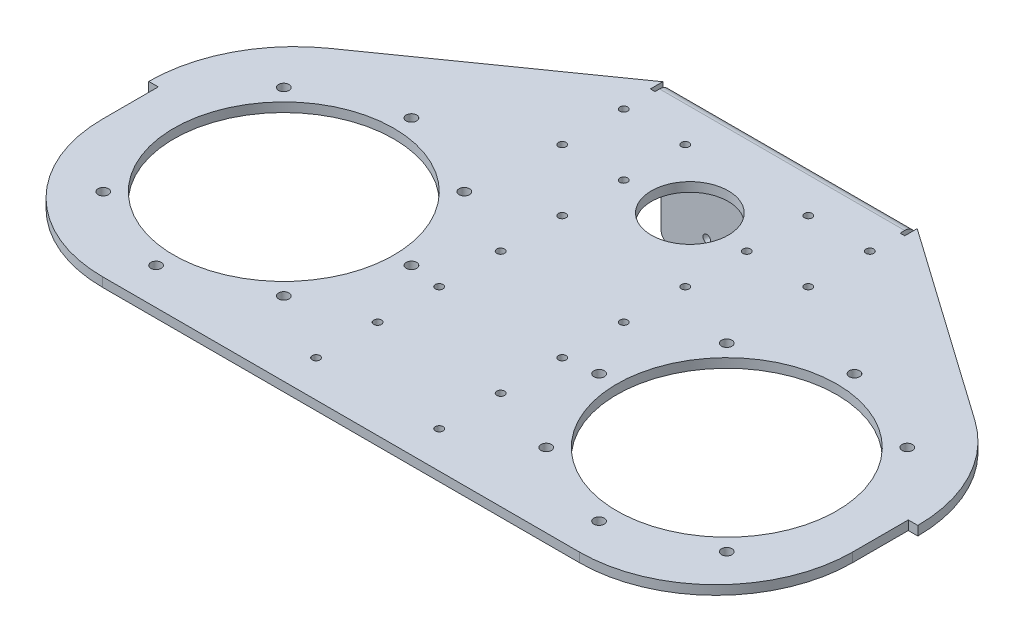
SolidWorks part; units mm, degrees
ref_plane "Спереди" through (0, 0, 0) normal (0, 0, 1) x (1, 0, 0)
ref_plane "Сверху" through (0, 0, 0) normal (0, 1, 0) x (1, 0, 0)
ref_plane "Справа" through (0, 0, 0) normal (1, 0, 0) x (0, 0, -1)
ref_plane "Плоскость4" through (0, 3, 0) normal (0, 1, 0) x (1, 0, 0)
sketch "Эскиз1" plane through (0, 3, 0) normal (0, 1, 0) x (1, 0, 0)
  line L0 (-124.9999, 9.1) -> (124.9999, 9.1)
  line L1 (104.8475, 47.8377) -> (41.3416, 92.5553)
  line L2 (41.3416, 92.5553) -> (41.3416, 88.5)
  line L3 (41.3416, 88.5) -> (-41.3416, 88.5)
  line L4 (-41.3416, 88.5) -> (-41.3416, 92.5553)
  line L5 (-41.3416, 92.5553) -> (-104.8475, 47.8377)
  arc A0 (124.9999, 9.1) -> (104.8475, 47.8377) centre (77.5, 9) ccw
  arc A1 (-104.8475, 47.8377) -> (-124.9999, 9.1) centre (-77.5, 9) ccw
extrude "Бобышка-Вытянуть1" add sketch "Эскиз1" against normal blind 3
sketch "Эскиз2" plane through (0, 0, -9.1) normal (0, 0, 1) x (1, 0, 0)
  line L0 (-121.9, 3) -> (121.9, 3)
  line L1 (121.9, 3) -> (121.9, 0)
  line L2 (121.9, 0) -> (-121.9, 0)
  line L3 (-121.9, 0) -> (-121.9, 3)
extrude "Бобышка-Вытянуть2" add sketch "Эскиз2" along normal blind 62.5
sketch "Эскиз3" plane through (0, 0, -88.5) normal (0, 0, -1) x (-1, 0, 0)
  line L0 (-39.8416, 0) -> (-39.8416, 3)
  line L1 (-39.8416, 3) -> (39.8416, 3)
  line L2 (39.8416, 3) -> (39.8416, 0)
  line L3 (39.8416, 0) -> (-39.8416, 0)
extrude "Бобышка-Вытянуть3" add sketch "Эскиз3" along normal blind 5
sketch "Эскиз4" plane through (0, 0, 0) normal (0, -1, 0) x (1, 0, 0)
  line L0 (39.8416, -93.5) -> (-39.8416, -93.5)
  line L1 (-39.8416, -93.5) -> (-39.8416, -90.5)
  line L2 (-39.8416, -90.5) -> (39.8416, -90.5)
  line L3 (39.8416, -90.5) -> (39.8416, -93.5)
extrude "Бобышка-Вытянуть4" add sketch "Эскиз4" along normal blind 40
hole_wizard "Диаметр отверстия Ø2.5 (2.5)1" positions "Эскиз6" profile "Эскиз5" hole size "Ø2.5" standard "Ansi Metric"
sketch "Эскиз6" plane through (0, 0, -90.5) normal (0, 0, 1) x (1, 0, 0)
  point P0 (25, -16)
  point P1 (25, -32)
  point P2 (0, -16)
  point P3 (0, -32)
  point P4 (-25, -16)
  point P5 (-25, -32)
sketch "Эскиз5" plane through (25, -16, -90.5) normal (1, 0, 0) x (0, -1, 0)
  line L0 (0, 0) -> (0, 3)
  line L1 (0, 3) -> (1.25, 3)
  line L2 (1.25, 3) -> (1.25, 0)
  line L5 (1.25, 0) -> (0, 0)
  line L11 (0, -6.35) -> (0, 107.95) construction
  dimension "Диаметр сквозного отверстия" = 2.5
  dimension "Глубина сквозного отверстия" = 3
hole_wizard "Диаметр отверстия Ø2.5 (2.5)2" positions "Эскиз8" profile "Эскиз7" hole size "Ø2.5" standard "Ansi Metric"
sketch "Эскиз8" plane through (0, 3, 0) normal (0, 1, 0) x (1, 0, 0)
  point P0 (-40, 78.5)
  point P1 (20, -41.5)
  point P2 (-20, -41.5)
  point P3 (20, -21.5)
  point P4 (-20, -21.5)
  point P5 (20, -1.5)
  point P6 (-20, -1.5)
  point P7 (20, 18.5)
  point P8 (-20, 18.5)
  point P9 (20, 38.5)
  point P10 (-20, 38.5)
  point P11 (40, 58.5)
  point P12 (40, 78.5)
  point P13 (20, 58.5)
  point P14 (20, 78.5)
  point P15 (-20, 58.5)
  point P16 (-20, 78.5)
  point P17 (-40, 58.5)
sketch "Эскиз7" plane through (-40, 3, -78.5) normal (1, 0, 0) x (0, 0, 1)
  line L0 (0, 0) -> (0, 43)
  line L1 (0, 43) -> (1.25, 43)
  line L2 (1.25, 43) -> (1.25, 0)
  line L5 (1.25, 0) -> (0, 0)
  line L11 (0, -6.35) -> (0, 107.95) construction
  dimension "Диаметр сквозного отверстия" = 2.5
  dimension "Глубина сквозного отверстия" = 43
hole_wizard "Диаметр отверстия Ø25.0 (25)1" positions "Эскиз10" profile "Эскиз9" hole size "Ø25.0" standard "Ansi Metric"
sketch "Эскиз10" plane through (0, 3, 0) normal (0, 1, 0) x (1, 0, 0)
  point P0 (0, 60)
sketch "Эскиз9" plane through (0, 3, -60) normal (1, 0, 0) x (0, 0, 1)
  line L0 (0, 0) -> (0, 43)
  line L1 (0, 43) -> (12.5, 43)
  line L2 (12.5, 43) -> (12.5, 0)
  line L5 (12.5, 0) -> (0, 0)
  line L11 (0, -6.35) -> (0, 107.95) construction
  dimension "Диаметр сквозного отверстия" = 25
  dimension "Глубина сквозного отверстия" = 43
hole_wizard "Диаметр отверстия Ø3.4 (3.4)1" positions "Эскиз12" profile "Эскиз11" hole size "Ø3.4" standard "Ansi Metric"
sketch "Эскиз12" plane through (0, 3, 0) normal (0, 1, 0) x (1, 0, 0)
  point P0 (-72, 41.5)
  point P1 (-101.3449, 29.3449)
  point P2 (-101.3449, -29.3449)
  point P3 (-72, -41.5)
  point P4 (-42.6551, -29.3449)
  point P5 (-30.5, 0)
  point P6 (-42.6551, 29.3449)
  point P7 (72, 41.5)
  point P8 (101.3449, 29.3449)
  point P9 (101.3449, -29.3449)
  point P10 (72, -41.5)
  point P11 (42.6551, -29.3449)
  point P12 (30.5, 0)
  point P13 (42.6551, 29.3449)
sketch "Эскиз11" plane through (-72, 3, -41.5) normal (1, 0, 0) x (0, 0, 1)
  line L0 (0, 0) -> (0, 43)
  line L1 (0, 43) -> (1.7, 43)
  line L2 (1.7, 43) -> (1.7, 0)
  line L5 (1.7, 0) -> (0, 0)
  line L11 (0, -6.35) -> (0, 107.95) construction
  dimension "Диаметр сквозного отверстия" = 3.4
  dimension "Глубина сквозного отверстия" = 43
hole_wizard "Отверстие с зазором M641" positions "Эскиз14" profile "Эскиз13" hole size "M64" standard "Ansi Metric"
sketch "Эскиз14" plane through (0, 0, 0) normal (0, -1, 0) x (-1, 0, 0)
  point P0 (72, 0)
  point P1 (-72, 0)
sketch "Эскиз13" plane through (-72, 0, 0) normal (1, 0, 0) x (0, 0, -1)
  line L0 (0, 0) -> (0, 3)
  line L1 (0, 3) -> (35.75, 3)
  line L2 (35.75, 3) -> (35.75, 0)
  line L5 (35.75, 0) -> (0, 0)
  line L11 (0, -6.35) -> (0, 107.95) construction
  dimension "Диаметр сквозного отверстия" = 71.5
  dimension "Глубина сквозного отверстия" = 3
fillet "Скругление1" radius 0.5 1 edges at (0, 0, -90.5)
fillet "Скругление2" radius 3 2 edges at (39.8416, -40, -92) (-39.8416, -40, -92)
fillet "Скругление3" radius 3.5 1 edges at (0, 3, -93.5)
fillet "Скругление4" radius 44.4 2 edges at (-121.9, 1.5, 53.4) (121.9, 1.5, 53.4)
